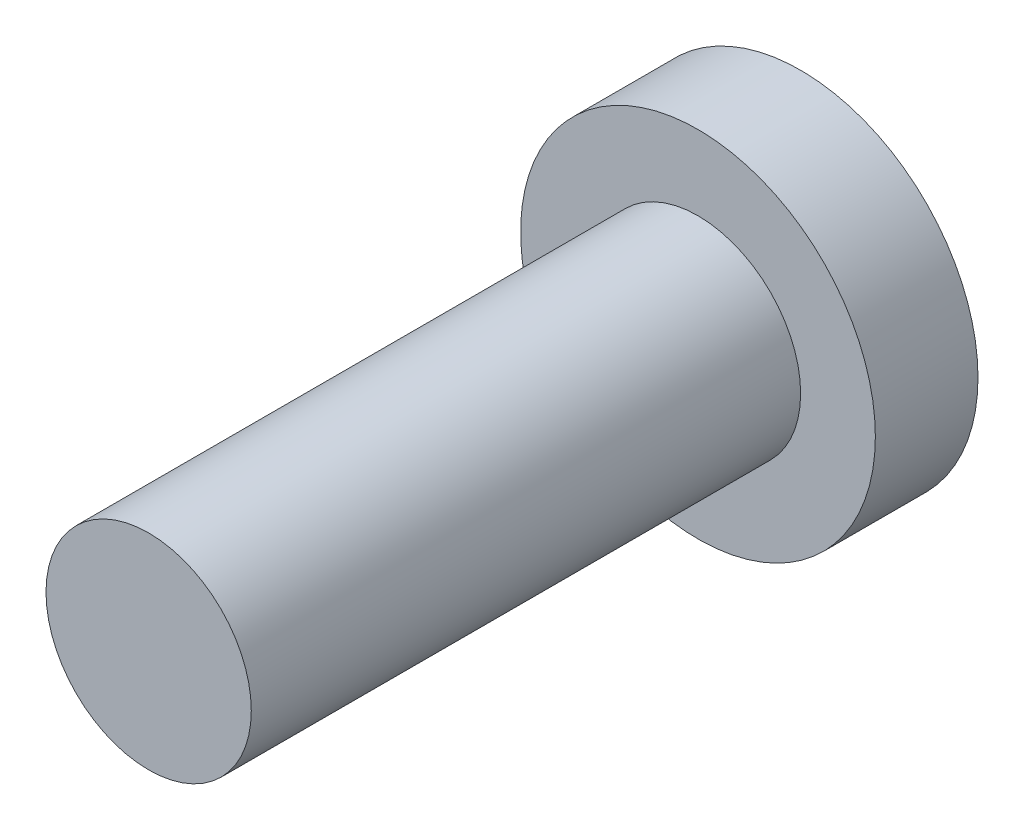
SolidWorks part; units mm, degrees
ref_plane "Front Plane" through (0, 0, 0) normal (0, 0, 1) x (1, 0, 0)
ref_plane "Top Plane" through (0, 0, 0) normal (0, 1, 0) x (1, 0, 0)
ref_plane "Right Plane" through (0, 0, 0) normal (1, 0, 0) x (0, 0, -1)
sketch "Sketch1" plane through (0, 0, 0) normal (0, 0, 1) x (1, 0, 0)
  circle A0 centre (0, 0) radius 4.32
extrude "Head" add sketch "Sketch1" along normal blind 2.5
ref_plane "Plane_z2_5" through (0, 0, 2.5) normal (0, 0, 1) x (1, 0, 0)
sketch "Sketch2" plane through (0, 0, 2.5) normal (0, 0, 1) x (1, 0, 0)
  circle A0 centre (0, 0) radius 2.5
extrude "Shank" add sketch "Sketch2" along normal blind 13.38
